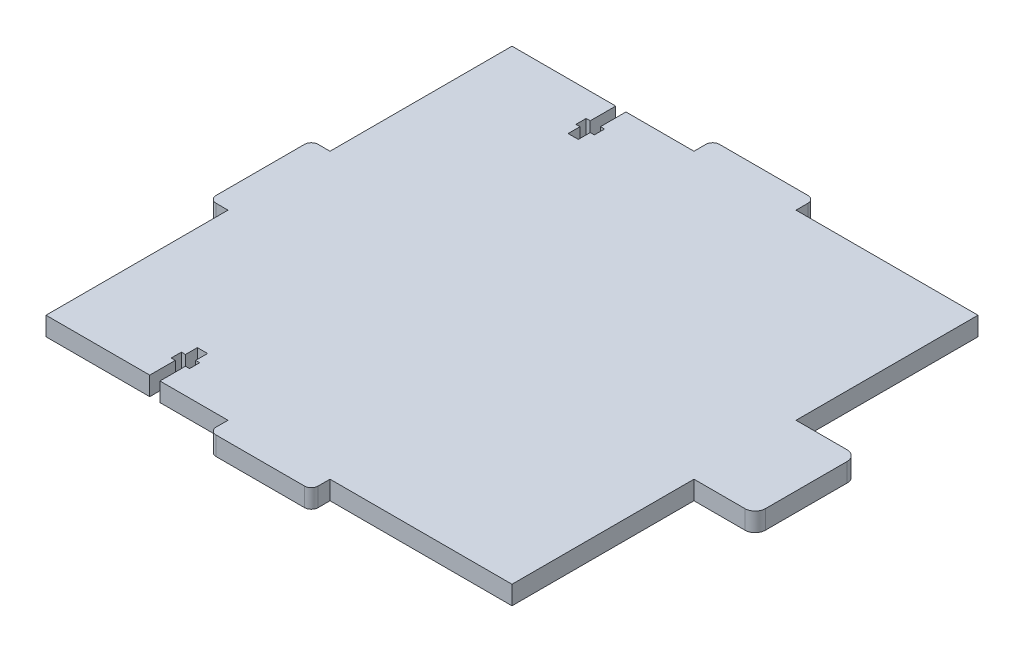
SolidWorks part; units mm, degrees
ref_plane "Front Plane" through (0, 0, 0) normal (0, 0, 1) x (1, 0, 0)
ref_plane "Top Plane" through (0, 0, 0) normal (0, 1, 0) x (1, 0, 0)
ref_plane "Right Plane" through (0, 0, 0) normal (1, 0, 0) x (0, 0, -1)
sketch "Sketch1" plane through (0, 0, 0) normal (0, 1, 0) x (1, 0, 0)
  line L0 (0, 83.5) -> (0, 137)
  line L1 (0, 0) -> (30.5, 0)
  line L2 (0, 0) -> (0, 53.5)
  line L3 (0, 137) -> (30.5, 137)
  line L4 (137, 0) -> (137, 53.5)
  line L5 (33.5, 137) -> (53.5, 137)
  line L6 (53.5, 0) -> (53.5, -5.5)
  line L7 (53.5, -5.5) -> (83.5, -5.5)
  line L8 (83.5, 0) -> (83.5, -5.5)
  line L9 (137, 83.5) -> (137, 137)
  line L10 (53.5, 137) -> (53.5, 142.5)
  line L11 (53.5, 142.5) -> (83.5, 142.5)
  line L12 (83.5, 137) -> (83.5, 142.5)
  line L13 (137, 83.5) -> (155, 83.5)
  line L14 (83.5, 0) -> (137, 0)
  line L15 (137, 53.5) -> (155, 53.5)
  line L16 (155, 83.5) -> (155, 53.5)
  line L17 (0, 83.5) -> (-5.5, 83.5)
  line L18 (83.5, 137) -> (137, 137)
  line L19 (0, 53.5) -> (-5.5, 53.5)
  line L20 (-5.5, 83.5) -> (-5.5, 53.5)
  line L21 (33.5, 10.5) -> (34.7, 10.5)
  line L22 (33.5, 137) -> (33.5, 129.5)
  line L23 (33.5, 123) -> (30.5, 123)
  line L24 (30.5, 137) -> (30.5, 129.5)
  line L25 (30.5, 10.5) -> (30.5, 14)
  line L26 (33.5, 0) -> (33.5, 7.5)
  line L27 (33.5, 14) -> (30.5, 14)
  line L28 (30.5, 0) -> (30.5, 7.5)
  line L29 (29.3, 129.5) -> (30.5, 129.5)
  line L30 (29.3, 129.5) -> (29.3, 126.5)
  line L31 (29.3, 126.5) -> (30.5, 126.5)
  line L32 (34.7, 129.5) -> (34.7, 126.5)
  line L33 (33.5, 129.5) -> (34.7, 129.5)
  line L34 (33.5, 126.5) -> (34.7, 126.5)
  line L35 (30.5, 126.5) -> (30.5, 123)
  line L36 (33.5, 126.5) -> (33.5, 123)
  line L38 (29.3, 10.5) -> (30.5, 10.5)
  line L39 (29.3, 10.5) -> (29.3, 7.5)
  line L40 (29.3, 7.5) -> (30.5, 7.5)
  line L41 (34.7, 10.5) -> (34.7, 7.5)
  line L42 (33.5, 7.5) -> (34.7, 7.5)
  line L43 (33.5, 0) -> (53.5, 0)
  line L44 (33.5, 10.5) -> (33.5, 14)
  dimension "D1" = 137
  dimension "D2" = 137
  dimension "D3" = 30
  dimension "D4" = 5.5
  dimension "D5" = 53.5
  dimension "D6" = 53.5
  dimension "D7" = 30
  dimension "D8" = 5.5
  dimension "D9" = 18
  dimension "D10" = 30
  dimension "D11" = 53.5
  dimension "D12" = 53.5
  dimension "D13" = 30
  dimension "D14" = 5.5
  dimension "D15" = 3
  dimension "D16" = 3
  dimension "D17" = 20
  dimension "D18" = 20
  dimension "D19" = 14
  dimension "D20" = 14
  dimension "D21" = 1.2
  dimension "D22" = 5.4
  dimension "D23" = 7.5
  dimension "D24" = 3
  dimension "D25" = 1.2
  dimension "D26" = 5.4
  dimension "D27" = 3
  dimension "D28" = 7.5
extrude "Boss-Extrude1" add sketch "Sketch1" along normal blind 5.5
fillet "Fillet1" radius 2 6 edges at (83.5, 2.75, -142.5) (53.5, 2.75, -142.5) (-5.5, 2.75, -83.5) (-5.5, 2.75, -53.5) (53.5, 2.75, 5.5) (83.5, 2.75, 5.5)
fillet "Fillet2" radius 3 2 edges at (155, 2.75, -83.5) (155, 2.75, -53.5)
